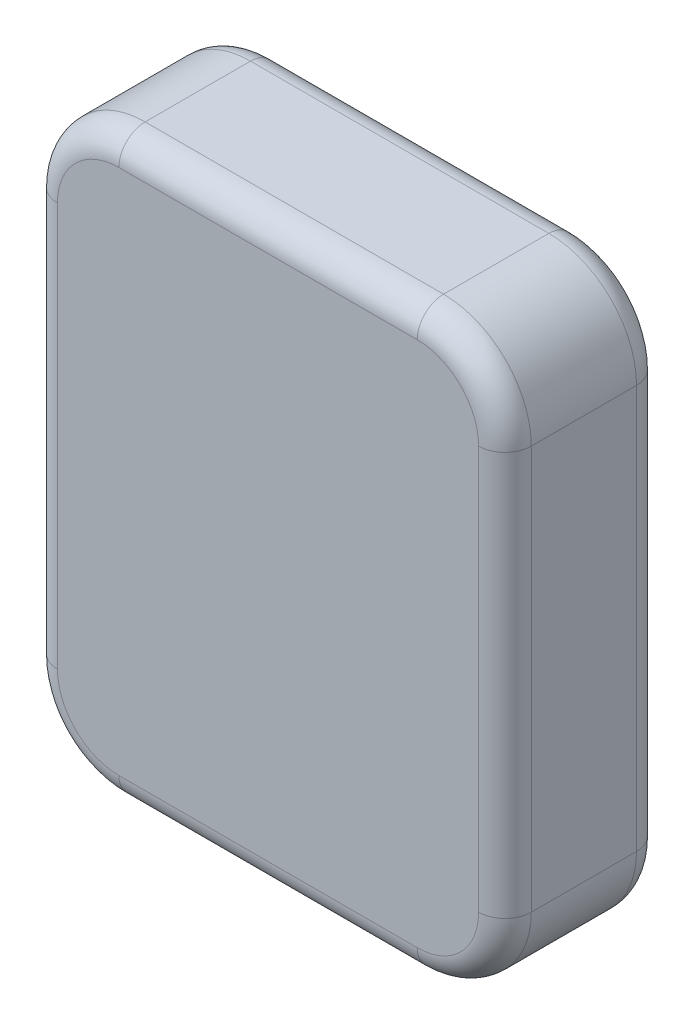
SolidWorks part; units mm, degrees
ref_plane "前视基准面" through (0, 0, 0) normal (0, 0, 1) x (1, 0, 0)
ref_plane "上视基准面" through (0, 0, 0) normal (0, 1, 0) x (1, 0, 0)
ref_plane "右视基准面" through (0, 0, 0) normal (1, 0, 0) x (0, 0, -1)
other "Configuration Table"
sketch "草图1" plane through (0, 0, 0) normal (0, 0, 1) x (1, 0, 0)
  line L1 (0, 0) -> (54, 0)
  line L2 (0, 0) -> (0, 66)
  line L3 (0, 66) -> (54, 66)
  line L4 (54, 0) -> (54, 66)
  dimension "D1" = 54
  dimension "D2" = 66
extrude "凸台-拉伸1" add sketch "草图1" along normal blind 18
fillet "圆角1" radius 10 4 edges at (0, 0, 9) (54, 0, 9) (54, 66, 9) (0, 66, 9)
fillet "圆角2" radius 3 16 edges at (51.0711, 2.9289, 0) (54, 33, 0) (51.0711, 63.0711, 0) (27, 66, 0) (2.9289, 63.0711, 0) (0, 33, 0) (2.9289, 2.9289, 0) (27, 0, 0) (2.9289, 63.0711, 18) (27, 66, 18) (51.0711, 63.0711, 18) (54, 33, 18) (51.0711, 2.9289, 18) (27, 0, 18) (2.9289, 2.9289, 18) (0, 33, 18)
